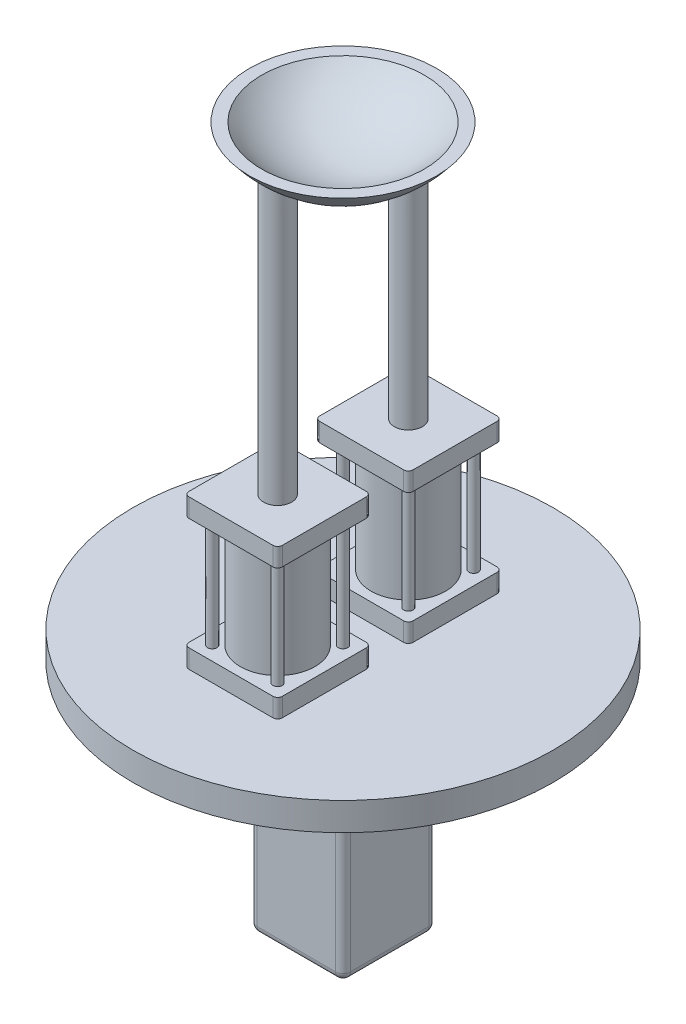
SolidWorks part; units mm, degrees
ref_plane "Front Plane" through (0, 0, 0) normal (0, 0, 1) x (1, 0, 0)
ref_plane "Top Plane" through (0, 0, 0) normal (0, 1, 0) x (1, 0, 0)
ref_plane "Right Plane" through (0, 0, 0) normal (1, 0, 0) x (0, 0, -1)
sketch "Sketch1" plane through (0, 0, 0) normal (0, 1, 0) x (1, 0, 0)
  circle A0 centre (0, 0) radius 225
  dimension "D1" = 450
extrude "Boss-Extrude1" add sketch "Sketch1" along normal blind 30
sketch "Sketch7" plane through (0, 0, 0) normal (1, 0, 0) x (0, 0, -1)
  line L0 (0, 228.9013) -> (0, 0) construction
  line L1 (0, 0) -> (319.3432, 0) construction
  line L2 (0, 450) -> (262.7708, 450) construction
  line L3 (100, 500) -> (0, 500)
  line L4 (0, 500) -> (0, 450)
  arc A0 (0, 450) -> (100, 500) centre (0, 575) ccw
  dimension "D1" = 100
  dimension "D3" = 450
  dimension "D2" = 50
revolve "Revolve1" add sketch "Sketch7" angle 360 about L4
shell "Shell1" thickness 10
sketch "Sketch8" plane through (0, 30, 0) normal (0, 1, 0) x (1, 0, 0)
  line L0 (0, 225) -> (0, 0) construction
  line L1 (0, 0) -> (225, 0) construction
  line L7 (-50, -120) -> (50, -20) construction
  line L8 (-50, 20) -> (50, 20)
  line L12 (-50, 20) -> (-50, 120)
  line L13 (-50, 120) -> (50, 120)
  line L26 (50, 20) -> (50, 120)
  line L27 (-50, 20) -> (50, 120) construction
  line L28 (-50, 120) -> (50, 20) construction
  line L29 (-50, -20) -> (50, -120) construction
  line L30 (50, -20) -> (50, -120)
  line L31 (-50, -120) -> (50, -120)
  line L32 (-50, -20) -> (-50, -120)
  line L33 (-50, -20) -> (50, -20)
  circle A0 centre (0, 0) radius 225 construction
  point P7 (0, 70)
  point P16 (0, -70)
  dimension "D1" = 100
  dimension "D2" = 100
  dimension "D3" = 20
extrude "Boss-Extrude2" add sketch "Sketch8" along normal blind 20 separate body
sketch "Sketch9" plane through (0, 0, 0) normal (0, -1, 0) x (1, 0, 0)
  circle A0 centre (0, 0) radius 17.5
  dimension "D1" = 35
extrude "Boss-Extrude3" add sketch "Sketch9" along normal blind 100 separate body
sketch "Sketch11" plane through (0, -100, 0) normal (0, -1, 0) x (1, 0, 0)
  line L1 (-50, -50) -> (50, -50)
  line L2 (-50, -50) -> (-50, 50)
  line L3 (-50, 50) -> (50, 50)
  line L4 (50, -50) -> (50, 50)
  line L5 (-50, -50) -> (50, 50) construction
  line L6 (-50, 50) -> (50, -50) construction
  point P0 (0, 0)
  dimension "D1" = 100
  dimension "D2" = 100
extrude "Boss-Extrude4" add sketch "Sketch11" along normal blind 150 separate body
fillet "Fillet1" radius 8 4 edges at (-50, -175, 50) (-50, -175, -50) (50, -175, -50) (50, -175, 50)
fillet "Fillet2" radius 8 8 edges at (47.6569, -250, 47.6569) (50, -250, 0) (47.6569, -250, -47.6569) (0, -250, -50) (-47.6569, -250, -47.6569) (-50, -250, 0) (-47.6569, -250, 47.6569) (0, -250, 50)
sketch "Sketch14" plane through (0, 50, 0) normal (0, 1, 0) x (1, 0, 0)
  line L0 (-50, 70) -> (50, 70) construction
  line L1 (-50, 120) -> (-50, 20) construction
  line L2 (50, 20) -> (50, 120) construction
  circle A0 centre (0, 70) radius 40
  dimension "D1" = 80
extrude "Boss-Extrude6" add sketch "Sketch14" along normal blind 120 separate body
sketch "Sketch15" plane through (0, 170, 0) normal (0, 1, 0) x (1, 0, 0)
  line L1 (-50, 120) -> (50, 120)
  line L2 (-50, 120) -> (-50, 20)
  line L3 (-50, 20) -> (50, 20)
  line L4 (50, 120) -> (50, 20)
extrude "Boss-Extrude7" add sketch "Sketch15" along normal blind 20 separate body
mirror "Mirror1" about plane through (0, 0, 0) normal (0, 0, 1) of bodies 117 116
sketch "Sketch16" plane through (0, 190, 0) normal (0, 1, 0) x (1, 0, 0)
  line L0 (-50, 70) -> (50, 70) construction
  line L1 (-50, 120) -> (-50, 20) construction
  line L2 (50, 20) -> (50, 120) construction
  line L3 (0, 0) -> (177.8967, 0) construction
  circle A0 centre (0, 70) radius 15
  circle A1 centre (0, -70) radius 15
  dimension "D1" = 30
extrude "Boss-Extrude8" add sketch "Sketch16" along normal up to surface (272.7503 mm away)
fillet "Fillet3" radius 5 8 edges at (-50, 180, 20) (-50, 180, 120) (50, 180, 120) (50, 180, 20) (50, 180, -20) (-50, 180, -20) (-50, 180, -120) (50, 180, -120)
fillet "Fillet4" radius 5 4 edges at (50, 40, -20) (-50, 40, -20) (-50, 40, -120) (50, 40, -120)
fillet "Fillet5" radius 5 4 edges at (50, 40, 120) (50, 40, 20) (-50, 40, 120) (-50, 40, 20)
sketch "Sketch17" plane through (0, 50, 0) normal (0, 1, 0) x (1, 0, 0)
  line L0 (0, 120) -> (0, 70) construction
  line L1 (45, 120) -> (-45, 120) construction
  line L2 (0, 70) -> (50, 70) construction
  line L3 (50, 25) -> (50, 115) construction
  line L4 (-50, 115) -> (-50, 25) construction
  circle A0 centre (-35, 105) radius 5
  circle A3 centre (35, 105) radius 5
  circle A4 centre (35, 35) radius 5
  circle A5 centre (-35, 35) radius 5
  dimension "D1" = 10
  dimension "D2" = 15
  dimension "D3" = 15
extrude "Boss-Extrude9" add sketch "Sketch17" along normal up to surface (120 mm away) separate body up to face at (0, 170, -70)
mirror "Mirror3" about plane through (0, 0, 0) normal (0, 0, 1) of bodies 123 126 125 124
